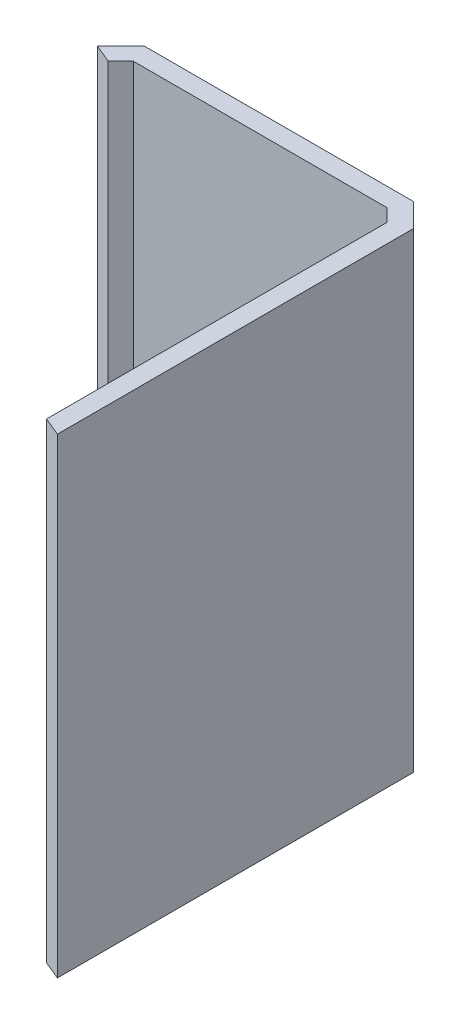
SolidWorks part; units mm, degrees
ref_plane "Front Plane" through (0, 0, 0) normal (0, 0, 1) x (1, 0, 0)
ref_plane "Top Plane" through (0, 0, 0) normal (0, 1, 0) x (1, 0, 0)
ref_plane "Right Plane" through (0, 0, 0) normal (1, 0, 0) x (0, 0, -1)
sketch "Sketch1" plane through (0, 0, 0) normal (0, 1, 0) x (1, 0, 0)
  line L0 (-25.0088, 95.4053) -> (-21.2324, 99.1817)
  line L1 (-21.2324, 99.1817) -> (22.2338, 99.1817)
  line L2 (22.2338, 99.1817) -> (26.0103, 95.4053)
  line L3 (26.0103, 95.4053) -> (26.0103, 37.9391)
  line L4 (26.0103, 37.9391) -> (23.0103, 39.1817)
  line L5 (23.0103, 39.1817) -> (23.0103, 94.1626)
  line L6 (23.0103, 94.1626) -> (20.9912, 96.1817)
  line L7 (20.9912, 96.1817) -> (-19.9897, 96.1817)
  line L8 (-19.9897, 96.1817) -> (-22.0088, 94.1626)
  line L9 (-22.0088, 94.1626) -> (-25.0088, 95.4053)
extrude "Boss-Extrude1" add sketch "Sketch1" along normal blind 76
